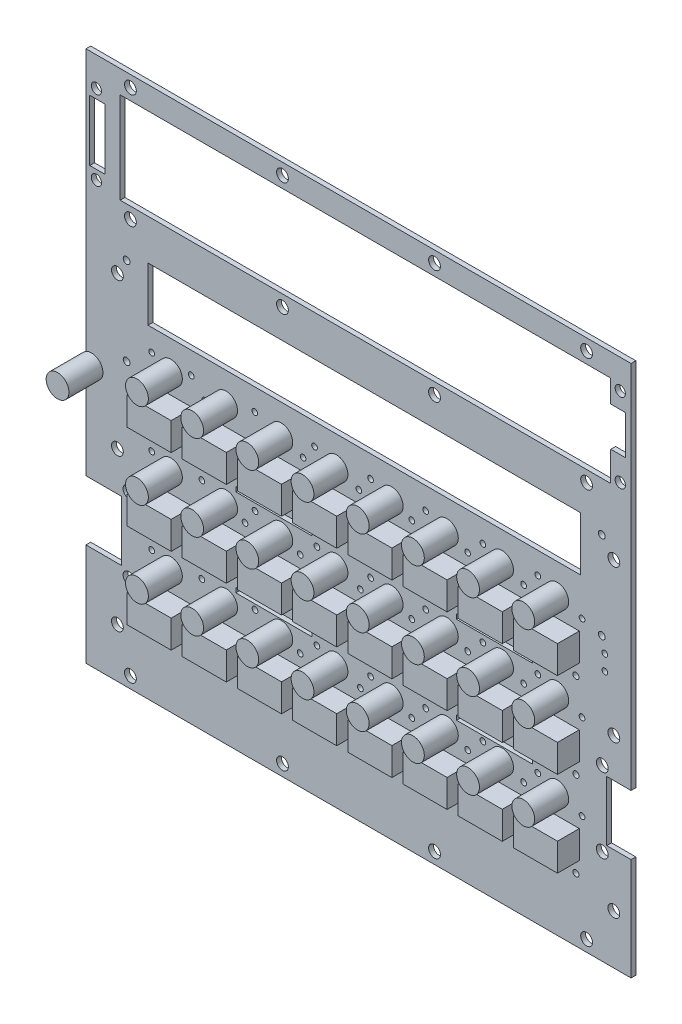
SolidWorks part; units mm, degrees
ref_plane "Front Plane" through (0, 0, 0) normal (0, 0, 1) x (1, 0, 0)
ref_plane "Top Plane" through (0, 0, 0) normal (0, 1, 0) x (1, 0, 0)
ref_plane "Right Plane" through (0, 0, 0) normal (1, 0, 0) x (0, 0, -1)
sketch "Sketch1" plane through (0, 0, 0) normal (0, 0, 1) x (1, 0, 0)
  line L0 (0, 0) -> (182.118, 0)
  line L1 (182.118, 0) -> (182.118, 34.2468)
  line L2 (182.118, 34.2468) -> (173.9875, 34.2468)
  line L3 (173.9875, 34.2468) -> (173.9875, 54.2468)
  line L4 (173.9875, 54.2468) -> (182.118, 54.2468)
  line L5 (182.118, 54.2468) -> (182.118, 177.8)
  line L6 (182.118, 177.8) -> (0, 177.8)
  line L7 (0, 177.8) -> (0, 54.2468)
  line L8 (0, 54.2468) -> (11.8694, 54.2468)
  line L9 (11.8694, 54.2468) -> (11.8694, 34.2468)
  line L10 (11.8694, 34.2468) -> (0, 34.2468)
  line L11 (0, 34.2468) -> (0, 0)
  line L12 (20.7391, 108.1786) -> (20.7391, 126.1796)
  line L13 (20.7391, 126.1796) -> (165.3007, 126.1796)
  line L14 (165.3007, 126.1796) -> (165.3007, 108.1786)
  line L15 (165.3007, 108.1786) -> (20.7391, 108.1786)
  line L16 (1.27, 144.653) -> (1.27, 164.973)
  line L17 (1.27, 164.973) -> (6.35, 164.973)
  line L18 (6.35, 164.973) -> (6.35, 144.653)
  line L19 (6.35, 144.653) -> (1.27, 144.653)
  line L20 (12.7, 170.18) -> (175.26, 170.18)
  line L21 (175.26, 170.18) -> (175.26, 162.6616)
  line L22 (175.26, 162.6616) -> (180.086, 162.6616)
  line L23 (180.086, 162.6616) -> (180.2892, 162.4584)
  line L24 (180.2892, 162.4584) -> (180.2892, 149.606)
  line L25 (180.2892, 149.606) -> (175.3616, 149.606)
  line L26 (175.3616, 149.606) -> (175.26, 149.5044)
  line L27 (175.26, 149.5044) -> (175.26, 139.7)
  line L28 (175.26, 139.7) -> (12.7, 139.7)
  line L29 (12.7, 139.7) -> (11.43, 139.7)
  line L30 (11.43, 139.7) -> (11.43, 170.18)
  line L31 (11.43, 170.18) -> (12.7, 170.18)
  line L32 (50.0634, 45.4152) -> (50.0634, 47.0027)
  line L33 (50.0634, 47.0027) -> (75.4634, 47.0027)
  line L34 (75.4634, 47.0027) -> (75.4634, 45.4152)
  line L35 (75.4634, 45.4152) -> (50.0634, 45.4152)
  line L36 (123.8134, 45.4152) -> (123.8134, 47.0027)
  line L37 (123.8134, 47.0027) -> (149.2134, 47.0027)
  line L38 (149.2134, 47.0027) -> (149.2134, 45.4152)
  line L39 (149.2134, 45.4152) -> (123.8134, 45.4152)
  line L40 (123.8134, 74.6252) -> (123.8134, 76.2127)
  line L41 (123.8134, 76.2127) -> (149.2134, 76.2127)
  line L42 (149.2134, 76.2127) -> (149.2134, 74.6252)
  line L43 (149.2134, 74.6252) -> (123.8134, 74.6252)
  line L44 (50.0634, 74.6252) -> (50.0634, 76.2127)
  line L45 (50.0634, 76.2127) -> (75.4634, 76.2127)
  line L46 (75.4634, 76.2127) -> (75.4634, 74.6252)
  line L47 (75.4634, 74.6252) -> (50.0634, 74.6252)
extrude "BOARD" add sketch "Sketch1" along normal blind 1.5921 separate body
ref_plane "Plane1" through (0, 0, 1.5921) normal (0, 0, 1) x (1, 0, 0)
sketch "Sketch2" plane through (0, 0, 1.5921) normal (0, 0, 1) x (1, 0, 0)
  circle A0 centre (1.8694, 86.9188) radius 3.81
extrude "LED-KINGBRIGHT_3P_2P54-1" add sketch "Sketch2" along normal blind 11.3538 separate body
sketch "Sketch3" plane through (0, 0, 1.5921) normal (0, 0, 1) x (1, 0, 0)
  circle A0 centre (157.4597, 41.1988) radius 3.81
extrude "LED-KINGBRIGHT_3P_2P54-2" add sketch "Sketch3" along normal blind 11.3538 separate body
sketch "Sketch4" plane through (0, 0, 1.5921) normal (0, 0, 1) x (1, 0, 0)
  circle A0 centre (139.0222, 41.1988) radius 3.81
extrude "LED-KINGBRIGHT_3P_2P54-3" add sketch "Sketch4" along normal blind 11.3538 separate body
sketch "Sketch5" plane through (0, 0, 1.5921) normal (0, 0, 1) x (1, 0, 0)
  circle A0 centre (120.5847, 41.1988) radius 3.81
extrude "LED-KINGBRIGHT_3P_2P54-4" add sketch "Sketch5" along normal blind 11.3538 separate body
sketch "Sketch6" plane through (0, 0, 1.5921) normal (0, 0, 1) x (1, 0, 0)
  circle A0 centre (102.1472, 41.1988) radius 3.81
extrude "LED-KINGBRIGHT_3P_2P54-5" add sketch "Sketch6" along normal blind 11.3538 separate body
sketch "Sketch7" plane through (0, 0, 1.5921) normal (0, 0, 1) x (1, 0, 0)
  circle A0 centre (157.4597, 69.7738) radius 3.81
extrude "LED-KINGBRIGHT_3P_2P54-6" add sketch "Sketch7" along normal blind 11.3538 separate body
sketch "Sketch8" plane through (0, 0, 1.5921) normal (0, 0, 1) x (1, 0, 0)
  circle A0 centre (139.0222, 69.7738) radius 3.81
extrude "LED-KINGBRIGHT_3P_2P54-7" add sketch "Sketch8" along normal blind 11.3538 separate body
sketch "Sketch9" plane through (0, 0, 1.5921) normal (0, 0, 1) x (1, 0, 0)
  circle A0 centre (120.5847, 69.7738) radius 3.81
extrude "LED-KINGBRIGHT_3P_2P54-8" add sketch "Sketch9" along normal blind 11.3538 separate body
sketch "Sketch10" plane through (0, 0, 1.5921) normal (0, 0, 1) x (1, 0, 0)
  circle A0 centre (102.1472, 69.7738) radius 3.81
extrude "LED-KINGBRIGHT_3P_2P54-9" add sketch "Sketch10" along normal blind 11.3538 separate body
sketch "Sketch11" plane through (0, 0, 1.5921) normal (0, 0, 1) x (1, 0, 0)
  circle A0 centre (83.7097, 41.1988) radius 3.81
extrude "LED-KINGBRIGHT_3P_2P54-10" add sketch "Sketch11" along normal blind 11.3538 separate body
sketch "Sketch12" plane through (0, 0, 1.5921) normal (0, 0, 1) x (1, 0, 0)
  circle A0 centre (65.2722, 41.1988) radius 3.81
extrude "LED-KINGBRIGHT_3P_2P54-11" add sketch "Sketch12" along normal blind 11.3538 separate body
sketch "Sketch13" plane through (0, 0, 1.5921) normal (0, 0, 1) x (1, 0, 0)
  circle A0 centre (46.8347, 41.1988) radius 3.81
extrude "LED-KINGBRIGHT_3P_2P54-12" add sketch "Sketch13" along normal blind 11.3538 separate body
sketch "Sketch14" plane through (0, 0, 1.5921) normal (0, 0, 1) x (1, 0, 0)
  circle A0 centre (28.3972, 41.1988) radius 3.81
extrude "LED-KINGBRIGHT_3P_2P54-13" add sketch "Sketch14" along normal blind 11.3538 separate body
sketch "Sketch15" plane through (0, 0, 1.5921) normal (0, 0, 1) x (1, 0, 0)
  circle A0 centre (83.7097, 69.7738) radius 3.81
extrude "LED-KINGBRIGHT_3P_2P54-14" add sketch "Sketch15" along normal blind 11.3538 separate body
sketch "Sketch16" plane through (0, 0, 1.5921) normal (0, 0, 1) x (1, 0, 0)
  circle A0 centre (65.2722, 69.7738) radius 3.81
extrude "LED-KINGBRIGHT_3P_2P54-15" add sketch "Sketch16" along normal blind 11.3538 separate body
sketch "Sketch17" plane through (0, 0, 1.5921) normal (0, 0, 1) x (1, 0, 0)
  circle A0 centre (46.8347, 69.7738) radius 3.81
extrude "LED-KINGBRIGHT_3P_2P54-16" add sketch "Sketch17" along normal blind 11.3538 separate body
sketch "Sketch18" plane through (0, 0, 1.5921) normal (0, 0, 1) x (1, 0, 0)
  circle A0 centre (28.3972, 69.7738) radius 3.81
extrude "LED-KINGBRIGHT_3P_2P54-17" add sketch "Sketch18" along normal blind 11.3538 separate body
sketch "Sketch19" plane through (0, 0, 1.5921) normal (0, 0, 1) x (1, 0, 0)
  circle A0 centre (157.4597, 98.3488) radius 3.81
extrude "LED-KINGBRIGHT_3P_2P54-18" add sketch "Sketch19" along normal blind 11.3538 separate body
sketch "Sketch20" plane through (0, 0, 1.5921) normal (0, 0, 1) x (1, 0, 0)
  circle A0 centre (139.0222, 98.3488) radius 3.81
extrude "LED-KINGBRIGHT_3P_2P54-19" add sketch "Sketch20" along normal blind 11.3538 separate body
sketch "Sketch21" plane through (0, 0, 1.5921) normal (0, 0, 1) x (1, 0, 0)
  circle A0 centre (120.5847, 98.3488) radius 3.81
extrude "LED-KINGBRIGHT_3P_2P54-20" add sketch "Sketch21" along normal blind 11.3538 separate body
sketch "Sketch22" plane through (0, 0, 1.5921) normal (0, 0, 1) x (1, 0, 0)
  circle A0 centre (102.1472, 98.3488) radius 3.81
extrude "LED-KINGBRIGHT_3P_2P54-21" add sketch "Sketch22" along normal blind 11.3538 separate body
sketch "Sketch23" plane through (0, 0, 1.5921) normal (0, 0, 1) x (1, 0, 0)
  circle A0 centre (83.7097, 98.3488) radius 3.81
extrude "LED-KINGBRIGHT_3P_2P54-22" add sketch "Sketch23" along normal blind 11.3538 separate body
sketch "Sketch24" plane through (0, 0, 1.5921) normal (0, 0, 1) x (1, 0, 0)
  circle A0 centre (65.2722, 98.3488) radius 3.81
extrude "LED-KINGBRIGHT_3P_2P54-23" add sketch "Sketch24" along normal blind 11.3538 separate body
sketch "Sketch25" plane through (0, 0, 1.5921) normal (0, 0, 1) x (1, 0, 0)
  circle A0 centre (46.8347, 98.3488) radius 3.81
extrude "LED-KINGBRIGHT_3P_2P54-24" add sketch "Sketch25" along normal blind 11.3538 separate body
sketch "Sketch26" plane through (0, 0, 1.5921) normal (0, 0, 1) x (1, 0, 0)
  circle A0 centre (28.3972, 98.3488) radius 3.81
extrude "LED-KINGBRIGHT_3P_2P54-25" add sketch "Sketch26" along normal blind 11.3538 separate body
sketch "Sketch27" plane through (0, 0, 1.5921) normal (0, 0, 1) x (1, 0, 0)
  line L0 (150.0937, 25.3238) -> (150.0937, 34.5948)
  line L1 (150.0937, 34.5948) -> (164.8257, 34.5948)
  line L2 (164.8257, 34.5948) -> (164.8257, 25.3238)
  line L3 (164.8257, 25.3238) -> (150.0937, 25.3238)
extrude "SWITCH-MCDTS2-1" add sketch "Sketch27" along normal blind 7.3 separate body
sketch "Sketch28" plane through (0, 0, 1.5921) normal (0, 0, 1) x (1, 0, 0)
  line L0 (150.0937, 53.8988) -> (150.0937, 63.1698)
  line L1 (150.0937, 63.1698) -> (164.8257, 63.1698)
  line L2 (164.8257, 63.1698) -> (164.8257, 53.8988)
  line L3 (164.8257, 53.8988) -> (150.0937, 53.8988)
extrude "SWITCH-MCDTS2-2" add sketch "Sketch28" along normal blind 7.3 separate body
sketch "Sketch29" plane through (0, 0, 1.5921) normal (0, 0, 1) x (1, 0, 0)
  line L0 (131.6562, 25.3238) -> (131.6562, 34.5948)
  line L1 (131.6562, 34.5948) -> (146.3882, 34.5948)
  line L2 (146.3882, 34.5948) -> (146.3882, 25.3238)
  line L3 (146.3882, 25.3238) -> (131.6562, 25.3238)
extrude "SWITCH-MCDTS2-3" add sketch "Sketch29" along normal blind 7.3 separate body
sketch "Sketch30" plane through (0, 0, 1.5921) normal (0, 0, 1) x (1, 0, 0)
  line L0 (113.2187, 25.3238) -> (113.2187, 34.5948)
  line L1 (113.2187, 34.5948) -> (127.9507, 34.5948)
  line L2 (127.9507, 34.5948) -> (127.9507, 25.3238)
  line L3 (127.9507, 25.3238) -> (113.2187, 25.3238)
extrude "SWITCH-MCDTS2-4" add sketch "Sketch30" along normal blind 7.3 separate body
sketch "Sketch31" plane through (0, 0, 1.5921) normal (0, 0, 1) x (1, 0, 0)
  line L0 (94.7812, 25.3238) -> (94.7812, 34.5948)
  line L1 (94.7812, 34.5948) -> (109.5132, 34.5948)
  line L2 (109.5132, 34.5948) -> (109.5132, 25.3238)
  line L3 (109.5132, 25.3238) -> (94.7812, 25.3238)
extrude "SWITCH-MCDTS2-5" add sketch "Sketch31" along normal blind 7.3 separate body
sketch "Sketch32" plane through (0, 0, 1.5921) normal (0, 0, 1) x (1, 0, 0)
  line L0 (76.3437, 25.3238) -> (76.3437, 34.5948)
  line L1 (76.3437, 34.5948) -> (91.0757, 34.5948)
  line L2 (91.0757, 34.5948) -> (91.0757, 25.3238)
  line L3 (91.0757, 25.3238) -> (76.3437, 25.3238)
extrude "SWITCH-MCDTS2-6" add sketch "Sketch32" along normal blind 7.3 separate body
sketch "Sketch33" plane through (0, 0, 1.5921) normal (0, 0, 1) x (1, 0, 0)
  line L0 (57.9062, 25.3238) -> (57.9062, 34.5948)
  line L1 (57.9062, 34.5948) -> (72.6382, 34.5948)
  line L2 (72.6382, 34.5948) -> (72.6382, 25.3238)
  line L3 (72.6382, 25.3238) -> (57.9062, 25.3238)
extrude "SWITCH-MCDTS2-7" add sketch "Sketch33" along normal blind 7.3 separate body
sketch "Sketch34" plane through (0, 0, 1.5921) normal (0, 0, 1) x (1, 0, 0)
  line L0 (39.4687, 25.3238) -> (39.4687, 34.5948)
  line L1 (39.4687, 34.5948) -> (54.2007, 34.5948)
  line L2 (54.2007, 34.5948) -> (54.2007, 25.3238)
  line L3 (54.2007, 25.3238) -> (39.4687, 25.3238)
extrude "SWITCH-MCDTS2-8" add sketch "Sketch34" along normal blind 7.3 separate body
sketch "Sketch35" plane through (0, 0, 1.5921) normal (0, 0, 1) x (1, 0, 0)
  line L0 (21.0312, 25.3238) -> (21.0312, 34.5948)
  line L1 (21.0312, 34.5948) -> (35.7632, 34.5948)
  line L2 (35.7632, 34.5948) -> (35.7632, 25.3238)
  line L3 (35.7632, 25.3238) -> (21.0312, 25.3238)
extrude "SWITCH-MCDTS2-9" add sketch "Sketch35" along normal blind 7.3 separate body
sketch "Sketch36" plane through (0, 0, 1.5921) normal (0, 0, 1) x (1, 0, 0)
  line L0 (131.6562, 53.8988) -> (131.6562, 63.1698)
  line L1 (131.6562, 63.1698) -> (146.3882, 63.1698)
  line L2 (146.3882, 63.1698) -> (146.3882, 53.8988)
  line L3 (146.3882, 53.8988) -> (131.6562, 53.8988)
extrude "SWITCH-MCDTS2-10" add sketch "Sketch36" along normal blind 7.3 separate body
sketch "Sketch37" plane through (0, 0, 1.5921) normal (0, 0, 1) x (1, 0, 0)
  line L0 (113.2187, 53.8988) -> (113.2187, 63.1698)
  line L1 (113.2187, 63.1698) -> (127.9507, 63.1698)
  line L2 (127.9507, 63.1698) -> (127.9507, 53.8988)
  line L3 (127.9507, 53.8988) -> (113.2187, 53.8988)
extrude "SWITCH-MCDTS2-11" add sketch "Sketch37" along normal blind 7.3 separate body
sketch "Sketch38" plane through (0, 0, 1.5921) normal (0, 0, 1) x (1, 0, 0)
  line L0 (94.7812, 53.8988) -> (94.7812, 63.1698)
  line L1 (94.7812, 63.1698) -> (109.5132, 63.1698)
  line L2 (109.5132, 63.1698) -> (109.5132, 53.8988)
  line L3 (109.5132, 53.8988) -> (94.7812, 53.8988)
extrude "SWITCH-MCDTS2-12" add sketch "Sketch38" along normal blind 7.3 separate body
sketch "Sketch39" plane through (0, 0, 1.5921) normal (0, 0, 1) x (1, 0, 0)
  line L0 (76.3437, 53.8988) -> (76.3437, 63.1698)
  line L1 (76.3437, 63.1698) -> (91.0757, 63.1698)
  line L2 (91.0757, 63.1698) -> (91.0757, 53.8988)
  line L3 (91.0757, 53.8988) -> (76.3437, 53.8988)
extrude "SWITCH-MCDTS2-13" add sketch "Sketch39" along normal blind 7.3 separate body
sketch "Sketch40" plane through (0, 0, 1.5921) normal (0, 0, 1) x (1, 0, 0)
  line L0 (57.9062, 53.8988) -> (57.9062, 63.1698)
  line L1 (57.9062, 63.1698) -> (72.6382, 63.1698)
  line L2 (72.6382, 63.1698) -> (72.6382, 53.8988)
  line L3 (72.6382, 53.8988) -> (57.9062, 53.8988)
extrude "SWITCH-MCDTS2-14" add sketch "Sketch40" along normal blind 7.3 separate body
sketch "Sketch41" plane through (0, 0, 1.5921) normal (0, 0, 1) x (1, 0, 0)
  line L0 (39.4687, 53.8988) -> (39.4687, 63.1698)
  line L1 (39.4687, 63.1698) -> (54.2007, 63.1698)
  line L2 (54.2007, 63.1698) -> (54.2007, 53.8988)
  line L3 (54.2007, 53.8988) -> (39.4687, 53.8988)
extrude "SWITCH-MCDTS2-15" add sketch "Sketch41" along normal blind 7.3 separate body
sketch "Sketch42" plane through (0, 0, 1.5921) normal (0, 0, 1) x (1, 0, 0)
  line L0 (21.0312, 53.8988) -> (21.0312, 63.1698)
  line L1 (21.0312, 63.1698) -> (35.7632, 63.1698)
  line L2 (35.7632, 63.1698) -> (35.7632, 53.8988)
  line L3 (35.7632, 53.8988) -> (21.0312, 53.8988)
extrude "SWITCH-MCDTS2-16" add sketch "Sketch42" along normal blind 7.3 separate body
sketch "Sketch43" plane through (0, 0, 1.5921) normal (0, 0, 1) x (1, 0, 0)
  line L0 (150.0937, 82.4738) -> (150.0937, 91.7448)
  line L1 (150.0937, 91.7448) -> (164.8257, 91.7448)
  line L2 (164.8257, 91.7448) -> (164.8257, 82.4738)
  line L3 (164.8257, 82.4738) -> (150.0937, 82.4738)
extrude "SWITCH-MCDTS2-17" add sketch "Sketch43" along normal blind 7.3 separate body
sketch "Sketch44" plane through (0, 0, 1.5921) normal (0, 0, 1) x (1, 0, 0)
  line L0 (131.6562, 82.4738) -> (131.6562, 91.7448)
  line L1 (131.6562, 91.7448) -> (146.3882, 91.7448)
  line L2 (146.3882, 91.7448) -> (146.3882, 82.4738)
  line L3 (146.3882, 82.4738) -> (131.6562, 82.4738)
extrude "SWITCH-MCDTS2-18" add sketch "Sketch44" along normal blind 7.3 separate body
sketch "Sketch45" plane through (0, 0, 1.5921) normal (0, 0, 1) x (1, 0, 0)
  line L0 (113.2187, 82.4738) -> (113.2187, 91.7448)
  line L1 (113.2187, 91.7448) -> (127.9507, 91.7448)
  line L2 (127.9507, 91.7448) -> (127.9507, 82.4738)
  line L3 (127.9507, 82.4738) -> (113.2187, 82.4738)
extrude "SWITCH-MCDTS2-19" add sketch "Sketch45" along normal blind 7.3 separate body
sketch "Sketch46" plane through (0, 0, 1.5921) normal (0, 0, 1) x (1, 0, 0)
  line L0 (94.7812, 82.4738) -> (94.7812, 91.7448)
  line L1 (94.7812, 91.7448) -> (109.5132, 91.7448)
  line L2 (109.5132, 91.7448) -> (109.5132, 82.4738)
  line L3 (109.5132, 82.4738) -> (94.7812, 82.4738)
extrude "SWITCH-MCDTS2-20" add sketch "Sketch46" along normal blind 7.3 separate body
sketch "Sketch47" plane through (0, 0, 1.5921) normal (0, 0, 1) x (1, 0, 0)
  line L0 (76.3437, 82.4738) -> (76.3437, 91.7448)
  line L1 (76.3437, 91.7448) -> (91.0757, 91.7448)
  line L2 (91.0757, 91.7448) -> (91.0757, 82.4738)
  line L3 (91.0757, 82.4738) -> (76.3437, 82.4738)
extrude "SWITCH-MCDTS2-21" add sketch "Sketch47" along normal blind 7.3 separate body
sketch "Sketch48" plane through (0, 0, 1.5921) normal (0, 0, 1) x (1, 0, 0)
  line L0 (57.9062, 82.4738) -> (57.9062, 91.7448)
  line L1 (57.9062, 91.7448) -> (72.6382, 91.7448)
  line L2 (72.6382, 91.7448) -> (72.6382, 82.4738)
  line L3 (72.6382, 82.4738) -> (57.9062, 82.4738)
extrude "SWITCH-MCDTS2-22" add sketch "Sketch48" along normal blind 7.3 separate body
sketch "Sketch49" plane through (0, 0, 1.5921) normal (0, 0, 1) x (1, 0, 0)
  line L0 (39.4687, 82.4738) -> (39.4687, 91.7448)
  line L1 (39.4687, 91.7448) -> (54.2007, 91.7448)
  line L2 (54.2007, 91.7448) -> (54.2007, 82.4738)
  line L3 (54.2007, 82.4738) -> (39.4687, 82.4738)
extrude "SWITCH-MCDTS2-23" add sketch "Sketch49" along normal blind 7.3 separate body
sketch "Sketch50" plane through (0, 0, 1.5921) normal (0, 0, 1) x (1, 0, 0)
  line L0 (21.0312, 82.4738) -> (21.0312, 91.7448)
  line L1 (21.0312, 91.7448) -> (35.7632, 91.7448)
  line L2 (35.7632, 91.7448) -> (35.7632, 82.4738)
  line L3 (35.7632, 82.4738) -> (21.0312, 82.4738)
extrude "SWITCH-MCDTS2-24" add sketch "Sketch50" along normal blind 7.3 separate body
sketch "Sketch56" plane through (0, 0, 1.5921) normal (0, 0, 1) x (1, 0, 0)
  circle B0 centre (163.703, 21.1074) radius 1.016
  circle B1 centre (163.703, 49.6824) radius 1.016
  circle B2 centre (145.2626, 21.8186) radius 0.9652
  circle B3 centre (126.8476, 21.6154) radius 0.9652
  circle B4 centre (108.4072, 21.7424) radius 0.9652
  circle B5 centre (89.9668, 21.844) radius 0.9652
  circle B6 centre (71.5264, 20.7772) radius 0.9652
  circle B7 centre (53.086, 21.1582) radius 0.9652
  circle B8 centre (34.6472, 21.1328) radius 1.016
  circle B9 centre (145.2626, 49.5554) radius 1.016
  circle B10 centre (126.8222, 49.3522) radius 1.016
  circle B11 centre (108.3818, 49.1236) radius 1.016
  circle B12 centre (89.9414, 49.6824) radius 1.016
  circle B13 centre (71.501, 49.1998) radius 1.016
  circle B14 centre (53.0606, 49.1998) radius 1.016
  circle B15 centre (34.6202, 49.276) radius 1.016
  circle B16 centre (163.703, 78.2574) radius 1.016
  circle B17 centre (145.2626, 77.7748) radius 1.016
  circle B18 centre (126.746, 78.3336) radius 1.016
  circle B19 centre (108.3818, 78.74) radius 1.016
  circle B20 centre (89.9414, 78.3336) radius 1.016
  circle B21 centre (71.501, 78.2574) radius 1.016
  circle B22 centre (53.0606, 78.4098) radius 1.016
  circle B23 centre (34.6202, 78.0542) radius 1.016
  circle B24 centre (91.694, 38.6588) radius 0.9525
  circle B25 centre (77.1652, 43.7388) radius 0.9525
  circle B26 centre (71.5772, 38.6588) radius 0.9525
  circle B27 centre (56.4896, 43.7388) radius 0.9525
  circle B28 centre (38.735, 43.7388) radius 0.9525
  circle B29 centre (21.8948, 38.6588) radius 0.9525
  circle B30 centre (21.971, 43.7388) radius 0.9525
  circle B31 centre (77.1652, 72.3138) radius 0.9525
  circle B32 centre (91.694, 67.2338) radius 0.9525
  circle B33 centre (71.5772, 67.2338) radius 0.9525
  circle B34 centre (56.4896, 72.3138) radius 0.9525
  circle B35 centre (53.1368, 67.2338) radius 0.9525
  circle B36 centre (38.735, 72.3138) radius 0.9525
  circle B37 centre (21.8948, 67.2338) radius 0.9525
  circle B38 centre (21.971, 72.3138) radius 0.9525
  circle B39 centre (165.735, 95.8088) radius 0.9525
  circle B40 centre (150.9776, 100.8888) radius 0.9525
  circle B41 centre (146.2278, 95.8088) radius 0.9525
  circle B42 centre (132.6134, 100.8888) radius 0.9525
  circle B43 centre (113.4872, 100.8888) radius 0.9525
  circle B44 centre (127.508, 95.8088) radius 0.9525
  circle B45 centre (108.8644, 95.8088) radius 0.9525
  circle B46 centre (95.0976, 100.8888) radius 0.9525
  circle B47 centre (91.186, 95.8088) radius 0.9525
  circle B48 centre (76.3778, 100.8888) radius 0.9525
  circle B49 centre (72.5424, 95.8088) radius 0.9525
  circle B50 centre (56.4134, 100.8888) radius 0.9525
  circle B51 centre (39.7256, 95.8088) radius 0.9525
  circle B52 centre (35.179, 100.8888) radius 0.9525
  circle B53 centre (24.2062, 95.8088) radius 0.9525
  circle B54 centre (21.971, 100.8888) radius 0.9525
  circle B55 centre (132.6134, 72.3138) radius 0.9525
  circle B56 centre (146.2278, 67.2338) radius 0.9525
  circle B57 centre (113.4872, 72.3138) radius 0.9525
  circle B58 centre (127.508, 67.2338) radius 0.9525
  circle B59 centre (95.0976, 72.3138) radius 0.9525
  circle B60 centre (108.8644, 67.2338) radius 0.9525
  circle B61 centre (150.9776, 43.7388) radius 0.9525
  circle B62 centre (132.6134, 43.7388) radius 0.9525
  circle B63 centre (113.4872, 43.7388) radius 0.9525
  circle B64 centre (95.0976, 43.7388) radius 0.9525
  circle B65 centre (108.8644, 38.6588) radius 0.9525
  circle B66 centre (150.9776, 72.3138) radius 0.9525
  circle B67 centre (165.735, 67.2338) radius 0.9525
  circle B68 centre (173.3296, 89.4588) radius 0.9525
  circle B69 centre (173.355, 84.3534) radius 0.9525
  circle B70 centre (176.3725, 118.11) radius 1.9685
  circle B71 centre (176.3725, 67.31) radius 1.9685
  circle B72 centre (176.3725, 16.51) radius 1.9685
  circle B73 centre (167.259, 135.89) radius 1.9685
  circle B74 centre (116.459, 135.89) radius 1.9685
  circle B75 centre (65.659, 135.89) radius 1.9685
  circle B76 centre (14.859, 135.89) radius 1.9685
  circle B77 centre (10.5105, 118.11) radius 1.9685
  circle B78 centre (10.5105, 67.31) radius 1.9685
  circle B79 centre (10.5105, 16.51) radius 1.9685
  circle B80 centre (165.735, 38.6588) radius 0.9525
  circle B81 centre (146.2278, 38.6588) radius 0.9525
  circle B82 centre (127.508, 38.6588) radius 0.9525
  circle B83 centre (14.859, 173.99) radius 1.9685
  circle B84 centre (65.659, 173.99) radius 1.9685
  circle B85 centre (116.459, 173.99) radius 1.9685
  circle B86 centre (167.259, 173.99) radius 1.9685
  circle B87 centre (167.259, 3.81) radius 1.9685
  circle B88 centre (116.459, 3.81) radius 1.9685
  circle B89 centre (65.659, 3.81) radius 1.9685
  circle B90 centre (14.859, 3.81) radius 1.9685
  circle B91 centre (172.5066, 56.7436) radius 1.9685
  circle B92 centre (172.5066, 31.75) radius 1.9685
  circle B93 centre (14.3688, 56.7436) radius 1.9685
  circle B94 centre (14.3688, 31.75) radius 1.9685
  circle B95 centre (172.3415, 123.3754) radius 1.1303
  circle B96 centre (172.3415, 94.1654) radius 1.1303
  circle B97 centre (13.5915, 94.1654) radius 1.1303
  circle B98 centre (13.5915, 123.3754) radius 1.1303
  circle B99 centre (178.5137, 141.5618) radius 1.7145
  circle B100 centre (178.5137, 168.0616) radius 1.7145
  circle B101 centre (3.5001, 168.0616) radius 1.7145
  circle B102 centre (3.5001, 141.5618) radius 1.7145
sketch_block_instance "Block-Model-1"
sketch_block "Block-Model"
extrude "Cut-Extrude1" cut sketch "Sketch56" against normal blind 10
